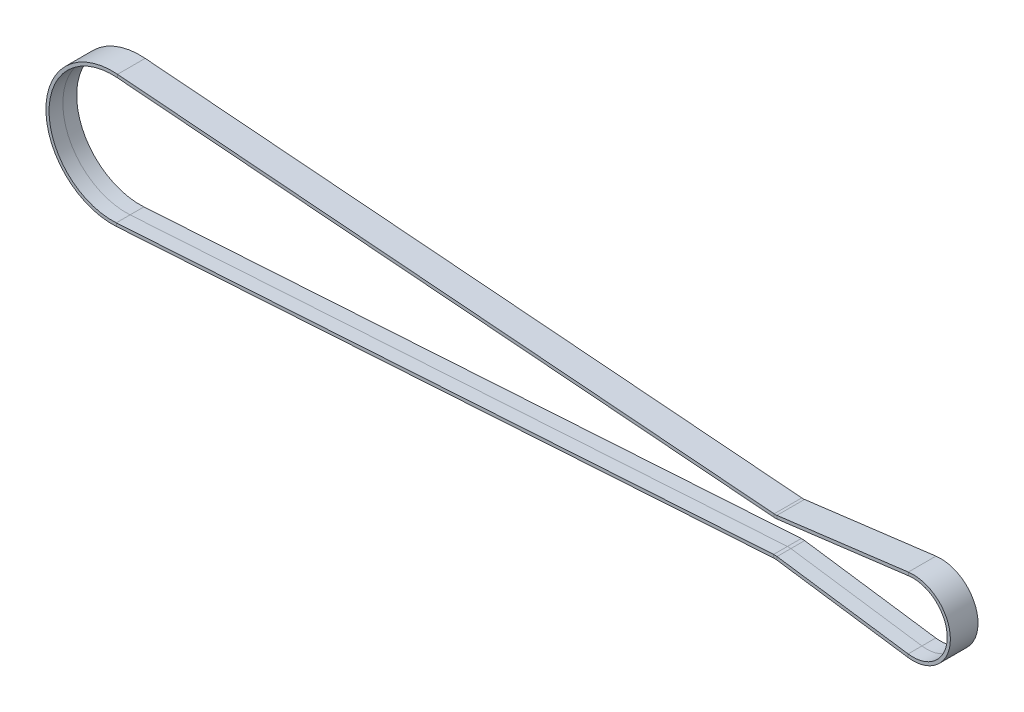
SolidWorks part; units mm, degrees
material "Rubber"
ref_plane "Front Plane" through (0, 0, 0) normal (0, 0, 1) x (1, 0, 0)
ref_plane "Top Plane" through (0, 0, 0) normal (0, 1, 0) x (1, 0, 0)
ref_plane "Right Plane" through (0, 0, 0) normal (1, 0, 0) x (0, 0, -1)
sketch "Sketch2" plane through (0, 0, 0) normal (0, 0, 1) x (1, 0, 0)
  line L0 (0, 0) -> (1, 0) construction
  line L1 (0, 0) -> (0, 1) construction
  line L2 (0.7608, -6.0221) -> (48.3458, -0.0105)
  line L3 (48.1427, -24.5876) -> (0.6636, -17.7904)
  line L4 (-0.5791, -17.7412) -> (-238.6473, -32.7709)
  line L5 (-238.2698, 12.9111) -> (-0.4825, -6.0508)
  arc A0 (-0.4825, -6.0508) -> (0.7608, -6.0221) centre (0, 0) ccw
  arc A1 (48.3458, -0.0105) -> (48.1427, -24.5876) centre (49.9, -12.3128) cw
  arc A2 (0.6636, -17.7904) -> (-0.5791, -17.7412) centre (-0.1967, -23.7992) ccw
  arc A3 (-238.6473, -32.7709) -> (-238.2698, 12.9111) centre (-240.0901, -9.9164) cw
ref_plane "Plane1" through (-238.2698, 12.9111, 0) normal (-0.9968, 0.0795, 0) x (0, 0, 1)
sketch "Sketch3" plane through (-238.2698, 12.9111, 0) normal (-0.9968, 0.0795, 0) x (0, 0, 1)
  line L0 (0, 0) -> (5, 0)
  line L1 (0, -45.8) -> (0, 0) construction
  line L2 (0, -14.6372) -> (0, 10.1628) construction
  line L3 (5, 0) -> (5, 1.14)
  line L4 (5, 1.14) -> (-5, 1.14)
  line L5 (-5, 1.14) -> (-5, 0)
  line L6 (-5, 0) -> (0, 0)
  dimension "D1" = 5
  dimension "D2" = 1.14
  dimension "D3" = 10
sweep "Sweep1" add profiles "Sketch3" path "Sketch2"
